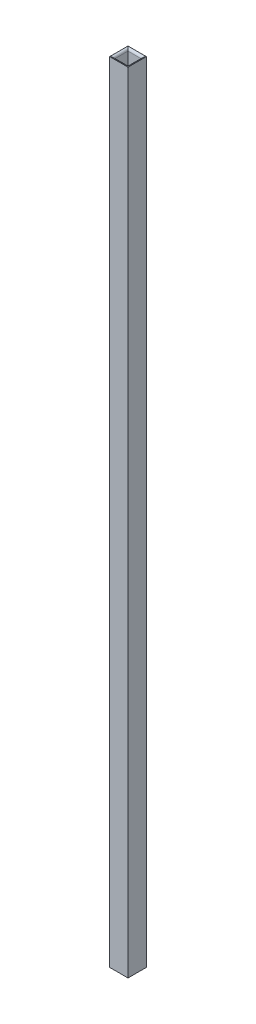
SolidWorks part; units mm, degrees
ref_plane "Front Plane" through (0, 0, 0) normal (0, 0, 1) x (1, 0, 0)
ref_plane "Top Plane" through (0, 0, 0) normal (0, 1, 0) x (1, 0, 0)
ref_plane "Right Plane" through (0, 0, 0) normal (1, 0, 0) x (0, 0, -1)
sketch "Sketch1" plane through (0, 0, 0) normal (0, 1, 0) x (1, 0, 0)
  line L1 (-15.5448, 16.8402) -> (-2.5448, 16.8402)
  line L2 (-15.5448, 16.8402) -> (-15.5448, 3.8402)
  line L3 (-15.5448, 3.8402) -> (-2.5448, 3.8402)
  line L4 (-2.5448, 16.8402) -> (-2.5448, 3.8402)
  line L5 (-9.0448, 3.8402) -> (-9.0448, 16.8402) construction
  line L6 (-15.5448, 10.3402) -> (-2.5448, 10.3402) construction
  point P164 (-9.0448, 10.3402)
  dimension "D1" = 13
  dimension "D2" = 13
extrude "Boss-Extrude1" add sketch "Sketch1" along normal blind 558.8
shell "Shell1" thickness 1.5875
fillet "Fillet1" radius 1.524 4 edges at (-13.9573, 0, -10.3402) (-9.0448, 0, -5.4277) (-4.1323, 0, -10.3402) (-9.0448, 0, -15.2527)
fillet "Fillet2" radius 1.524 4 edges at (-13.9573, 558.8, -10.3402) (-9.0448, 558.8, -5.4277) (-4.1323, 558.8, -10.3402) (-9.0448, 558.8, -15.2527)
